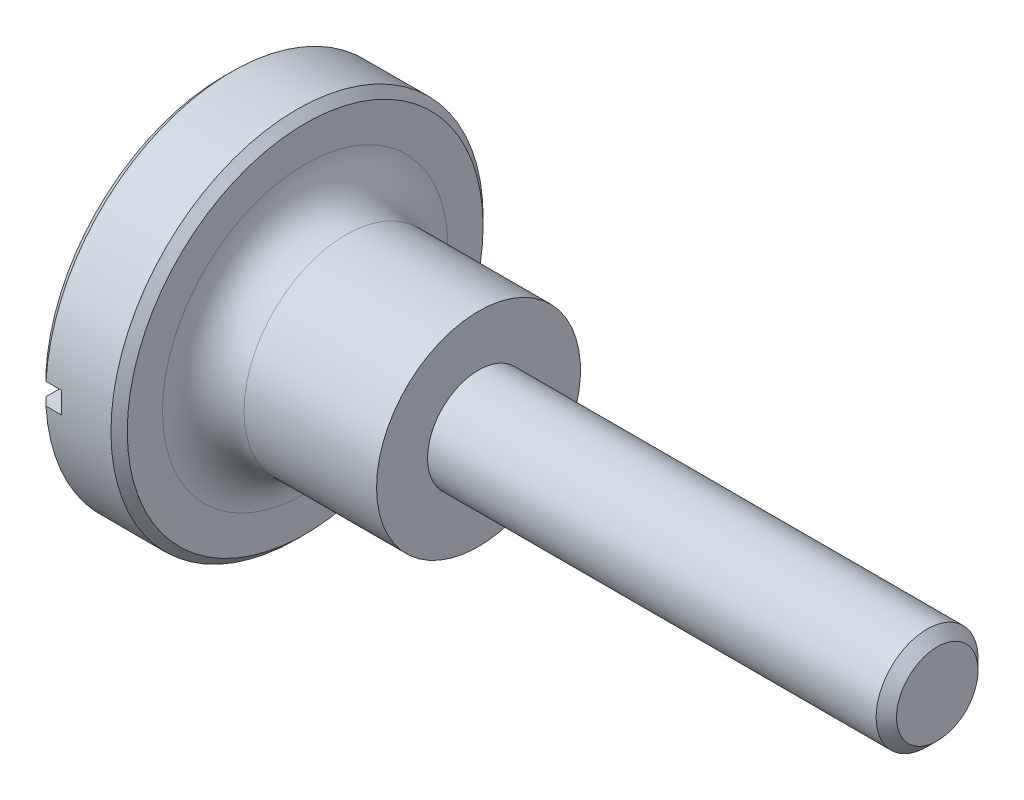
SolidWorks part; units mm, degrees
revolve "Base-Revolve" add sketch "BodySke" angle 360 about L2
sketch "BodySke" plane through (0, 0, 0) normal (0, 0, 1) x (1, 0, 0)
  line L0 (69, 5) -> (70, 4)
  line L1 (0, 0) -> (0, 17.45)
  line L2 (-25.4, 0) -> (127, 0) construction
  line L3 (70, 0) -> (0, 0)
  line L5 (70, 4) -> (70, 0)
  line L6 (0.8, 18.25) -> (7.2, 18.25)
  line L7 (4, 31.75) -> (4, -6.35) construction
  line L8 (0.8, 18.25) -> (0, 17.45)
  line L9 (10, 6.5875) -> (10, -2.9375) construction
  line L10 (30, 6.35) -> (30, -3.175) construction
  line L11 (7.2, 18.25) -> (8, 17.45)
  line L12 (8, 10) -> (25, 10)
  line L13 (25, 10) -> (25, 5)
  line L14 (25, 5) -> (69, 5)
  line L15 (8, 10) -> (8, 17.45)
  point P9 (70, 5)
  dimension "D1" = 45
  dimension "Chamfer" = 0.8
  dimension "Shoulder" = 25
  dimension "Thread_nom" = 40
  dimension "Head_ht" = 8
  dimension "diameter" = 10
  dimension "Ds" = 20
  dimension "Head_dia" = 36.5
  dimension "Advance" = 2
  dimension "Length" = 45
  dimension "D3" = 45
  dimension "Minor_dia" = 8
cosmetic thread "ThreadCosmetic" [suppressed] parameters "Thread_length"=40, "Thread_minor"=8
ref_plane "Plane1" through (0, 0, 0) normal (0, 0, 1) x (1, 0, 0)
ref_plane "Plane2" through (0, 0, 0) normal (0, 1, 0) x (1, 0, 0)
ref_plane "Plane3" through (0, 0, 0) normal (1, 0, 0) x (0, 0, -1)
sketch "ThdSchSke" plane through (0, 0, 0) normal (0, 0, 1) x (1, 0, 0)
  line L0 (30, -4) -> (29.2998, -5)
  line L1 (30, -4) -> (30.7002, -5)
  line L2 (30.7002, -5) -> (30.7002, -6.25)
  line L3 (-3.175, 0) -> (5.1513, 0) construction
  line L5 (30.7002, -6.25) -> (29.2998, -6.25)
  line L6 (29.2998, -6.25) -> (29.2998, -5)
  line L7 (25, -10) -> (25, 10) construction
  dimension "Thread_minor" = 8
  dimension "Diameter" = 10
  dimension "Start" = 5
revolve "ThreadSchematic" [suppressed] cut sketch "ThdSchSke" angle 360 about L3
pattern_linear "ThdSchPat" [suppressed]
sketch "KnurlSke" plane through (0, 0, 0) normal (-1, 0, 0) x (0, 0, 1)
  line L0 (0, 17.65) -> (0, 3.175) construction
  line L1 (0, 17.65) -> (0.3445, 18.2467)
  line L2 (0, 17.65) -> (-0.3445, 18.2467)
  line L3 (0, 18.25) -> (0, 17.65) construction
  circle A0 centre (0, 0) radius 18.25 construction
  arc A1 (0.3445, 18.2467) -> (-0.3445, 18.2467) centre (0, 0) ccw
  dimension "D2" = 60
extrude "Knurl_cut" [suppressed] cut sketch "KnurlSke" against normal up to next
pattern_circular "Knurl" [suppressed] count 86 over 360 about axis through (-25.4, 0, 0) along (1, 0, 0)
sketch "SlotSke" plane through (0, 0, 0) normal (0, 0, 1) x (1, 0, 0)
  line L0 (2.3466, 1.0507) -> (-2.3466, -1.0507) construction
  line L1 (-2.3466, -1.0507) -> (2.3466, -1.0507)
  line L2 (-2.3466, -1.0507) -> (-2.3466, 1.0507)
  line L3 (-2.3466, 1.0507) -> (2.3466, 1.0507)
  line L4 (2.3466, -1.0507) -> (2.3466, 1.0507)
  dimension "Slot_dep" = 2.3466
  dimension "Slot_Wid" = 2.1014
extrude "Slot" cut sketch "SlotSke" against normal through all and the other way through all
fillet "Fillet1" radius 4 1 edges at (8, 0, 10)
equation "\"Thread_minor@ThreadCosmetic\" = \"Minor_dia@BodySke\""
equation "\"Thread_length@ThreadCosmetic\" = ((sgn( (\"Length@BodySke\" - \"Advance@BodySke\" * 2.0 ) - \"Thread_nom@BodySke\" )-1)*( (\"Length@BodySke\" - \"Advance@BodySke\" * 2.0 ) - \"Thread_nom@BodySke\" ))/-2+ \"Thread_nom@BodySke\""
equation "\"Thread_minor@ThdSchSke\" = \"Thread_minor@ThreadCosmetic\""
equation "\"Diameter@ThdSchSke\" = \"diameter@BodySke\""
equation "\"Overcut@ThdSchSke\" = \"diameter@BodySke\" * 1.25"
equation "\"Start@ThdSchSke\" =  \"Length@BodySke\" -  \"Thread_length@ThreadCosmetic\"  '---Non-countersunk---"
equation "\"Num_threads@ThdSchPat\" = int( \"Thread_length@ThreadCosmetic\" / \"Advance@BodySke\" + 0.999 )  + 1"
equation "\"Advance@ThdSchPat\" = \"Thread_length@ThreadCosmetic\" /  (\"Num_threads@ThdSchPat\" - 1) 'relax it"
equation "\"depth@KnurlSke\" = \"Chamfer@BodySke\" * 0.75"
equation "\"Count@Knurl\" = (3.141592654 / 2 * \"Head_dia@BodySke\") / \"depth@KnurlSke\" * 0.9"
